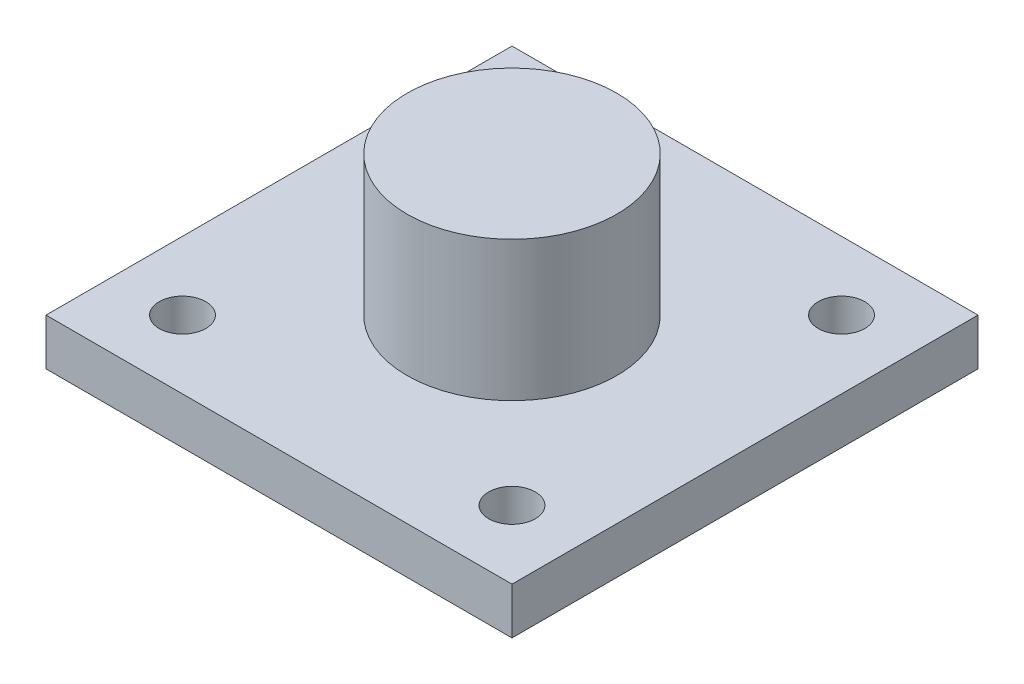
SolidWorks part; units mm, degrees
material "ABS PC"
ref_plane "Front Plane" through (0, 0, 0) normal (0, 0, 1) x (1, 0, 0)
ref_plane "Top Plane" through (0, 0, 0) normal (0, 1, 0) x (1, 0, 0)
ref_plane "Right Plane" through (0, 0, 0) normal (1, 0, 0) x (0, 0, -1)
sketch "Sketch1" plane through (0, 0, 0) normal (0, 1, 0) x (1, 0, 0)
  line L0 (0, 0) -> (0, 50) construction
  line L1 (-50, -50) -> (50, -50)
  line L2 (-50, -50) -> (-50, 50)
  line L3 (-50, 50) -> (50, 50)
  line L4 (50, -50) -> (50, 50)
  line L5 (-50, -50) -> (50, 50) construction
  line L6 (-50, 50) -> (50, -50) construction
  line L7 (0, 50) -> (0, 0) construction
  line L8 (0, 0) -> (50, 0) construction
  circle A0 centre (35.3553, 35.3553) radius 5
  circle A1 centre (-35.3553, 35.3553) radius 5
  circle A2 centre (-35.3553, -35.3553) radius 5
  circle A3 centre (35.3553, -35.3553) radius 5
  point P0 (0, 0)
  dimension "D2" = 10
  dimension "D1" = 100
  dimension "D3" = 50
extrude "Boss-Extrude1" add sketch "Sketch1" along normal blind 10
sketch "Sketch2" plane through (0, 10, 0) normal (0, 1, 0) x (1, 0, 0)
  circle A0 centre (0, 0) radius 22.5
  dimension "D1" = 45
extrude "Boss-Extrude2" add sketch "Sketch2" along normal blind 30
